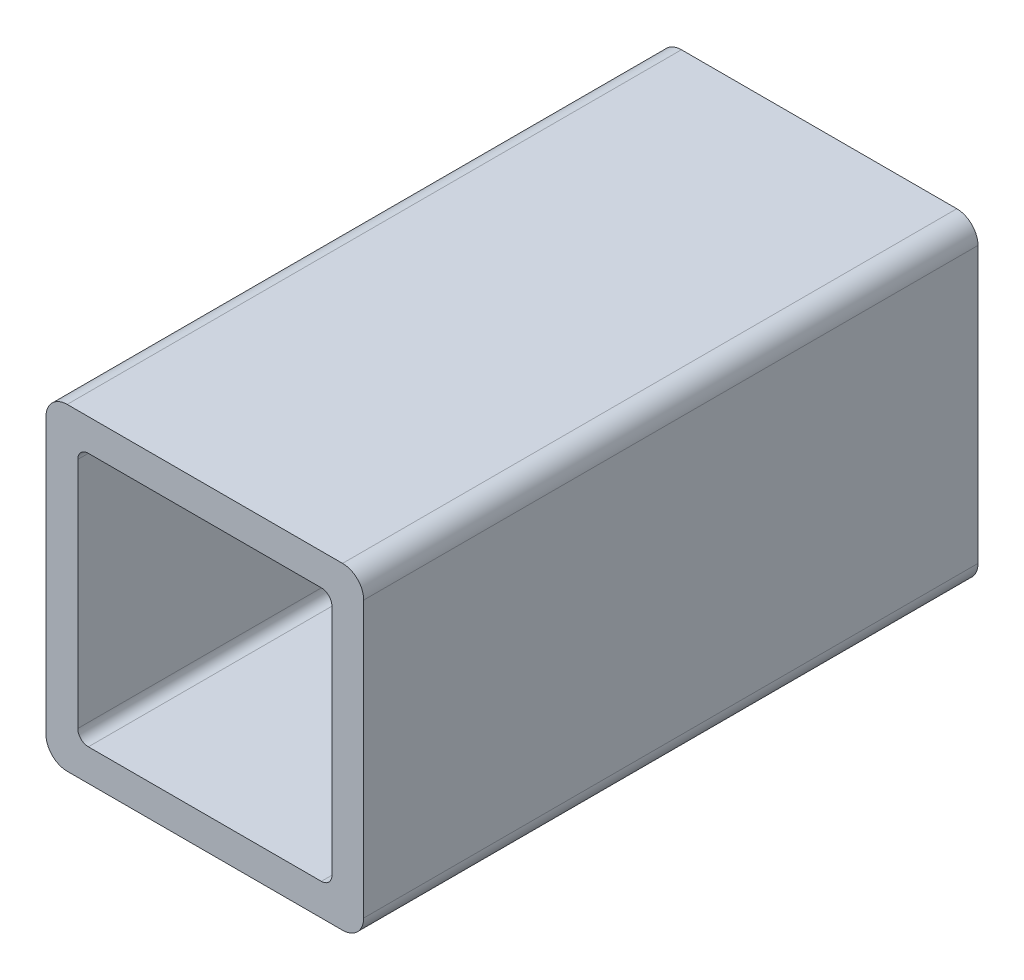
SolidWorks part; units mm, degrees
material "1.0553 (S355J0)"
ref_plane "Płaszczyzna przednia" through (0, 0, 0) normal (0, 0, 1) x (1, 0, 0)
ref_plane "Płaszczyzna górna" through (0, 0, 0) normal (0, 1, 0) x (1, 0, 0)
ref_plane "Płaszczyzna prawa" through (0, 0, 0) normal (1, 0, 0) x (0, 0, -1)
sketch "Szkic1" plane through (0, 0, 0) normal (0, 0, 1) x (1, 0, 0)
  line L1 (2, 0) -> (28, 0)
  line L2 (0, 2) -> (0, 28)
  line L3 (2, 30) -> (28, 30)
  line L4 (30, 2) -> (30, 28)
  line L5 (4, 3) -> (26, 3)
  line L6 (3, 4) -> (3, 26)
  line L7 (4, 27) -> (26, 27)
  line L8 (27, 4) -> (27, 26)
  arc A0 (0, 2) -> (2, 0) centre (2, 2) ccw
  arc A1 (28, 0) -> (30, 2) centre (28, 2) ccw
  arc A2 (30, 28) -> (28, 30) centre (28, 28) ccw
  arc A3 (2, 30) -> (0, 28) centre (2, 28) ccw
  arc A4 (3, 4) -> (4, 3) centre (4, 4) ccw
  arc A5 (26, 3) -> (27, 4) centre (26, 4) ccw
  arc A6 (27, 26) -> (26, 27) centre (26, 26) ccw
  arc A7 (4, 27) -> (3, 26) centre (4, 26) ccw
  point P7 (0, 0)
  point P12 (30, 30)
  point P15 (0, 30)
  dimension "D3" = 2
  dimension "D8" = 1
  dimension "D1" = 30
  dimension "D2" = 30
  dimension "D4" = 3
  dimension "D5" = 3
  dimension "D6" = 3
  dimension "D7" = 3
extrude "Dodanie-wyciągnięcie1" add sketch "Szkic1" along normal blind 58
